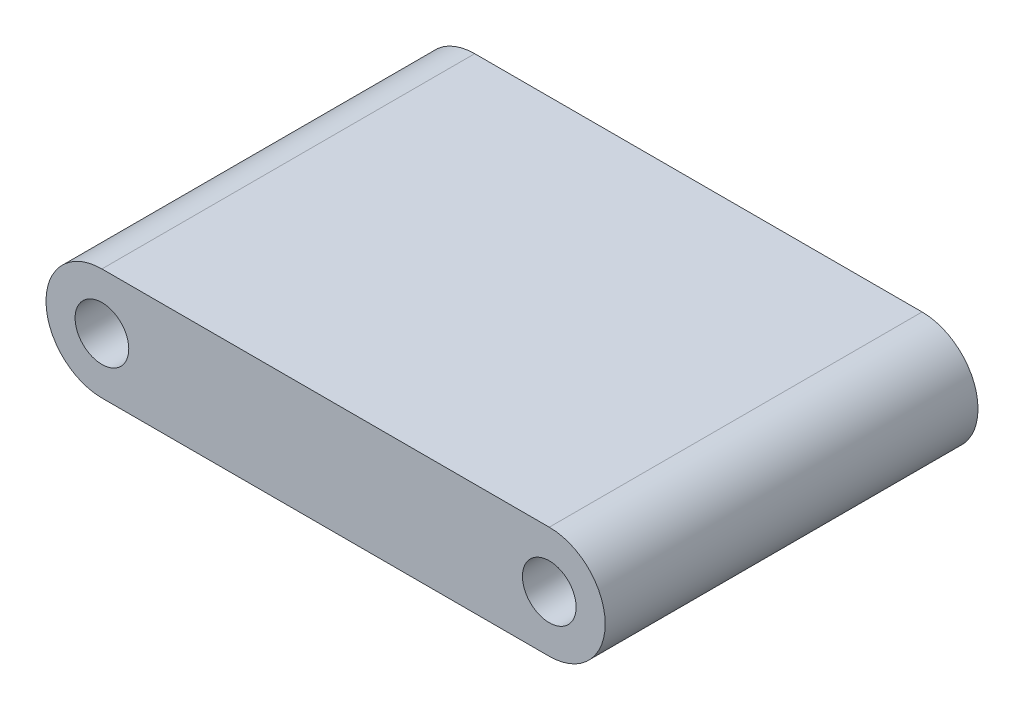
SolidWorks part; units mm, degrees
ref_plane "Front Plane" through (0, 0, 0) normal (0, 0, 1) x (1, 0, 0)
ref_plane "Top Plane" through (0, 0, 0) normal (0, 1, 0) x (1, 0, 0)
ref_plane "Right Plane" through (0, 0, 0) normal (1, 0, 0) x (0, 0, -1)
sketch "Sketch1" plane through (0, 0, 0) normal (0, 0, 1) x (1, 0, 0)
  line L0 (0, 0) -> (38.1, 0) construction
  line L1 (0, 4.7625) -> (38.1, 4.7625)
  line L2 (0, -4.7625) -> (38.1, -4.7625)
  arc A0 (0, 4.7625) -> (0, -4.7625) centre (0, 0) ccw
  arc A1 (38.1, -4.7625) -> (38.1, 4.7625) centre (38.1, 0) ccw
  circle A2 centre (0, 0) radius 2.286
  circle A3 centre (38.1, 0) radius 2.286
  point P3 (19.05, 0)
  dimension "D3" = 4.572
  dimension "D4" = 4.572
  dimension "D1" = 9.525
  dimension "D2" = 38.1
extrude "Boss-Extrude1" add sketch "Sketch1" along normal blind 31.75
